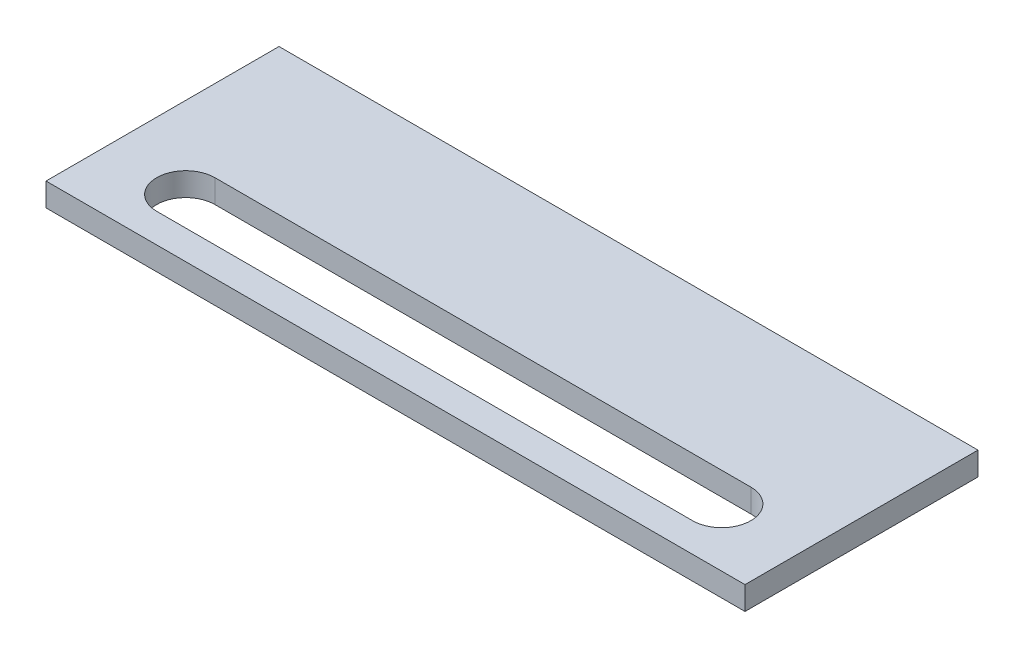
SolidWorks part; units mm, degrees
ref_plane "Front Plane" through (0, 0, 0) normal (0, 0, 1) x (1, 0, 0)
ref_plane "Top Plane" through (0, 0, 0) normal (0, 1, 0) x (1, 0, 0)
ref_plane "Right Plane" through (0, 0, 0) normal (1, 0, 0) x (0, 0, -1)
sketch "Sketch1" plane through (0, 0, 0) normal (0, 1, 0) x (1, 0, 0)
  line L0 (-55, 0) -> (55, 0) construction
  line L1 (-38.1, 0) -> (38.1, 0)
  line L2 (-38.1, 0) -> (-38.1, -25.4)
  line L3 (-38.1, -25.4) -> (38.1, -25.4)
  line L4 (38.1, 0) -> (38.1, -25.4)
  line L5 (0, -55) -> (0, 55) construction
  line L6 (-29.21, -19.05) -> (29.21, -19.05) construction
  line L7 (-29.21, -15.875) -> (29.21, -15.875)
  line L8 (-29.21, -22.225) -> (29.21, -22.225)
  arc A0 (-29.21, -15.875) -> (-29.21, -22.225) centre (-29.21, -19.05) ccw
  arc A1 (29.21, -22.225) -> (29.21, -15.875) centre (29.21, -19.05) ccw
  point P6 (0, -25.4)
  point P11 (0, -19.05)
  point P16 (0, 0)
  point P17 (0, 0)
  point P18 (0, 0)
  point P19 (-27.6197, -12.7)
  dimension "D1" = 19.05
  dimension "D2" = 6.35
  dimension "D3" = 25.4
  dimension "D4" = 76.2
  dimension "D5" = 8.89
extrude "Boss-Extrude1" add sketch "Sketch1" along normal blind 2.54
